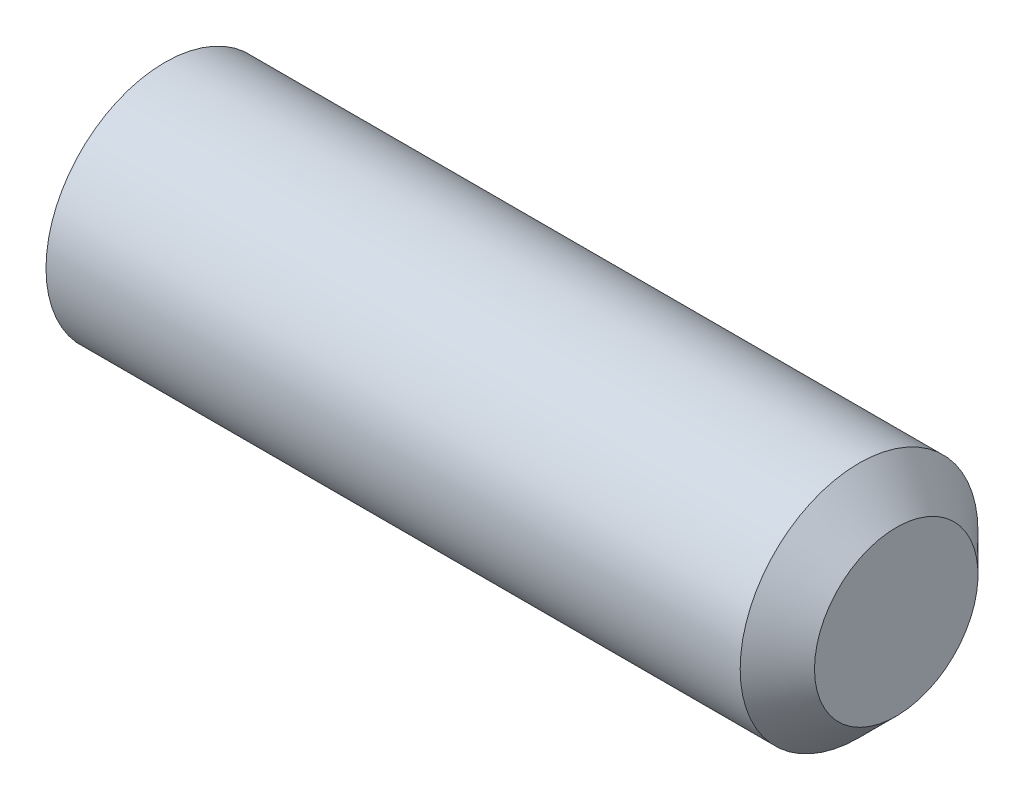
SolidWorks part; units mm, degrees
revolve "BaseBody" add sketch "BodySke" angle 360 about L5
sketch "BodySke" plane through (0, 0, 0) normal (0, 0, 1) x (1, 0, 0)
  line L0 (0, 0) -> (0, 3.3095)
  line L1 (0, 3.3095) -> (0.3987, 4)
  line L2 (0.3987, 4) -> (23.75, 4)
  line L3 (23.75, 4) -> (25, 2.75)
  line L4 (25, 0) -> (0, 0)
  line L5 (-12.7, 0) -> (88.9, 0) construction
  line L6 (25, 2.75) -> (25, 0)
  line L7 (25, 2.75) -> (25, 12.275) construction
  line L8 (0, -3.3095) -> (0.3987, -4) construction
  line L9 (1.25, 15.875) -> (1.25, -3.175) construction
  line L10 (23.75, -4) -> (25, -2.75) construction
  dimension "Diameter" = 8
  dimension "Drive_ch_ang" = 60
  dimension "Minor_dia" = 6.619
  dimension "Cup_nose_ang" = 45
  dimension "Cup_dia" = 5.5
  dimension "Length" = 25
  dimension "Advance" = 1.25
cosmetic thread "ThreadCosmetic" [suppressed] parameters "Thread_minor"=6.619
ref_plane "Plane1" through (0, 0, 0) normal (0, 0, 1) x (1, 0, 0)
ref_plane "Plane2" through (0, 0, 0) normal (0, 1, 0) x (1, 0, 0)
ref_plane "Plane3" through (0, 0, 0) normal (1, 0, 0) x (0, 0, -1)
other "Configuration Table"
sketch "Sketch2" plane through (0, 0, 0) normal (-1, 0, 0) x (0, 0, 1)
  line L0 (1.1547, 2) -> (-1.1547, 2)
  line L1 (-1.1547, 2) -> (-2.3094, 0)
  line L2 (1.1547, 2) -> (2.3094, 0)
  line L3 (1.1547, -2) -> (2.3094, 0)
  line L4 (1.1547, -2) -> (-1.1547, -2)
  line L5 (-1.1547, -2) -> (-2.3094, 0)
  dimension "Hex_size" = 4
  dimension "D2" = 2
  dimension "D3" = 2
extrude "Hex" cut sketch "Sketch2" against normal blind 4
sketch "Sketch4" plane through (0, 4.7709, -0.5249) normal (-1, 0, 0) x (0, 0, 1)
  line L0 (0.5249, -4.7709) -> (2.9124, -4.7709)
  line L1 (0.5249, -4.7709) -> (6.6732, -1.2211) construction
  line L2 (0.5249, -4.7709) -> (1.7186, -2.7032)
  line L3 (2.5132, -4.1951) -> (2.7953, -4.0322)
  line L4 (2.0177, -3.3368) -> (2.2998, -3.174)
  arc A0 (2.5132, -4.1951) -> (2.0177, -3.3368) centre (0.5249, -4.7709) ccw
  arc A1 (2.9124, -4.7709) -> (2.7953, -4.0322) centre (0.5249, -4.7709) ccw
  arc A2 (1.7186, -2.7032) -> (2.2998, -3.174) centre (0.5249, -4.7709) cw
  circle A3 centre (0.5249, -4.7709) radius 2.07 construction
  circle A4 centre (0.5249, -4.7709) radius 2.3875 construction
  dimension "Spline_n_dim" = 4.14
  dimension "Spline_m_dim" = 4.775
  dimension "D1" = 30
  dimension "Spline_a_dim" = 60
  dimension "Spline_p_dim" = 0.991
  dimension "D3" = 0.4955
extrude "Spline6" [suppressed] cut sketch "Sketch4" against normal blind 4
pattern_circular "CirPattern1" [suppressed] count 6 every 60 about axis through (-12.7, 0, 0) along (1, 0, 0)
sketch "Sketch5" plane through (0, 0.6556, 6.6316) normal (-1, 0, 0) x (0, 0, 1)
  line L0 (-6.6316, -0.6556) -> (-4.2441, -0.6556)
  line L1 (-6.6316, -0.6556) -> (-1.6115, 4.3645) construction
  line L2 (-6.6316, -0.6556) -> (-6.6316, 1.7319)
  line L3 (-4.8175, 0.4578) -> (-4.6298, 0.6455)
  line L4 (-5.5183, 1.1585) -> (-5.3305, 1.3463)
  line L5 (-5.5183, 1.1585) -> (-4.8175, 0.4578)
  arc A1 (-4.2441, -0.6556) -> (-4.6298, 0.6455) centre (-6.6316, -0.6556) ccw
  arc A2 (-6.6316, 1.7319) -> (-5.3305, 1.3463) centre (-6.6316, -0.6556) cw
  circle A3 centre (-6.6316, -0.6556) radius 2.07 construction
  circle A4 centre (-6.6316, -0.6556) radius 2.3875 construction
  dimension "Spline_n_dim" = 4.14
  dimension "Spline_m_dim" = 4.775
  dimension "Spline_p_dim" = 0.991
  dimension "D3" = 0.4955
  dimension "D1" = 45
  dimension "Spline_a_dim" = 90
extrude "Spline4" [suppressed] cut sketch "Sketch5" against normal blind 4
pattern_circular "CirPattern2" [suppressed] count 4 every 90 about axis through (-12.7, 0, 0) along (1, 0, 0)
sketch "ThdSchSke" plane through (0, 0, 0) normal (0, 0, 1) x (1, 0, 0)
  line L0 (0.3987, -3.3095) -> (-0.0848, -4)
  line L1 (0.3987, -3.3095) -> (0.8822, -4)
  line L2 (0.8822, -4) -> (0.8822, -5)
  line L3 (-3.175, 0) -> (5.1513, 0) construction
  line L4 (0.3987, 4) -> (0.3987, -4) construction
  line L5 (0.8822, -5) -> (-0.0848, -5)
  line L6 (-0.0848, -5) -> (-0.0848, -4)
  dimension "Thread_minor" = 6.619
  dimension "Diameter" = 8
revolve "ThreadSchematic" [suppressed] cut sketch "ThdSchSke" angle 360 about L3
pattern_linear "ThdSchPat" [suppressed]
equation "\"D2@Sketch2\" = \"Hex_size@Sketch2\" / 2"
equation "\"D3@Sketch2\" = \"Hex_size@Sketch2\" / 2"
equation "\"Thread_minor@ThreadCosmetic\" = \"Minor_dia@BodySke\""
equation "\"D1@Sketch4\" = \"Spline_a_dim@Sketch4\" / 2"
equation "\"D3@Sketch4\" = \"Spline_p_dim@Sketch4\" / 2"
equation "\"D2@CirPattern1\" = \"Spline_a_dim@Sketch4\""
equation "\"Num_teeth@CirPattern1\" = 360 / \"D2@CirPattern1\""
equation "\"Spline_a_dim@Sketch5\" = 90"
equation "\"Spline_p_dim@Sketch5\" = \"Spline_p_dim@Sketch4\""
equation "\"Spline_m_dim@Sketch5\" = \"Spline_m_dim@Sketch4\""
equation "\"Spline_n_dim@Sketch5\" = \"Spline_n_dim@Sketch4\""
equation "\"D1@Sketch5\" = \"Spline_a_dim@Sketch5\" / 2"
equation "\"D3@Sketch5\" = \"Spline_p_dim@Sketch5\" / 2"
equation "\"Key_eng@Spline4\" = \"Key_eng@Spline6\""
equation "\"Thread_minor@ThdSchSke\" = \"Thread_minor@ThreadCosmetic\""
equation "\"Diameter@ThdSchSke\" = \"Diameter@BodySke\""
equation "\"Overcut@ThdSchSke\" = \"Diameter@BodySke\" * 1.25"
equation "\"Num_threads@ThdSchPat\" = int( (\"Length@BodySke\" - ( ( ( \"Diameter@BodySke\" - \"Minor_dia@BodySke\" ) * 0.5 ) / tan( \"Drive_ch_ang@BodySke\" * 0.017453292 ) ) - ( ( ( \"Diameter@BodySke\" - \"Cup_dia@BodySke\" ) * 0.5 ) * tan( \"Cup_nose_ang@BodySke\" * 0.017453292 ) ) ) / \"Advance@BodySke\" + 0.999 )  + 1"
equation "\"Advance@ThdSchPat\" = (\"Length@BodySke\" - ( ( ( \"Diameter@BodySke\" - \"Minor_dia@BodySke\" ) * 0.5 ) / tan( \"Drive_ch_ang@BodySke\" * 0.017453292 ) ) - ( ( ( \"Diameter@BodySke\" - \"Cup_dia@BodySke\" ) * 0.5 ) * tan( \"Cup_nose_ang@BodySke\" * 0.017453292 ) ) ) /  (\"Num_threads@ThdSchPat\" - 1) 'relax it"
equation "' \"Num_threads@ThdSchPat\" = \"Num_threads@ThdSchPat\" - sgn( \"Num_threads@ThdSchPat\" - 1) '---chamfered tips only---"
